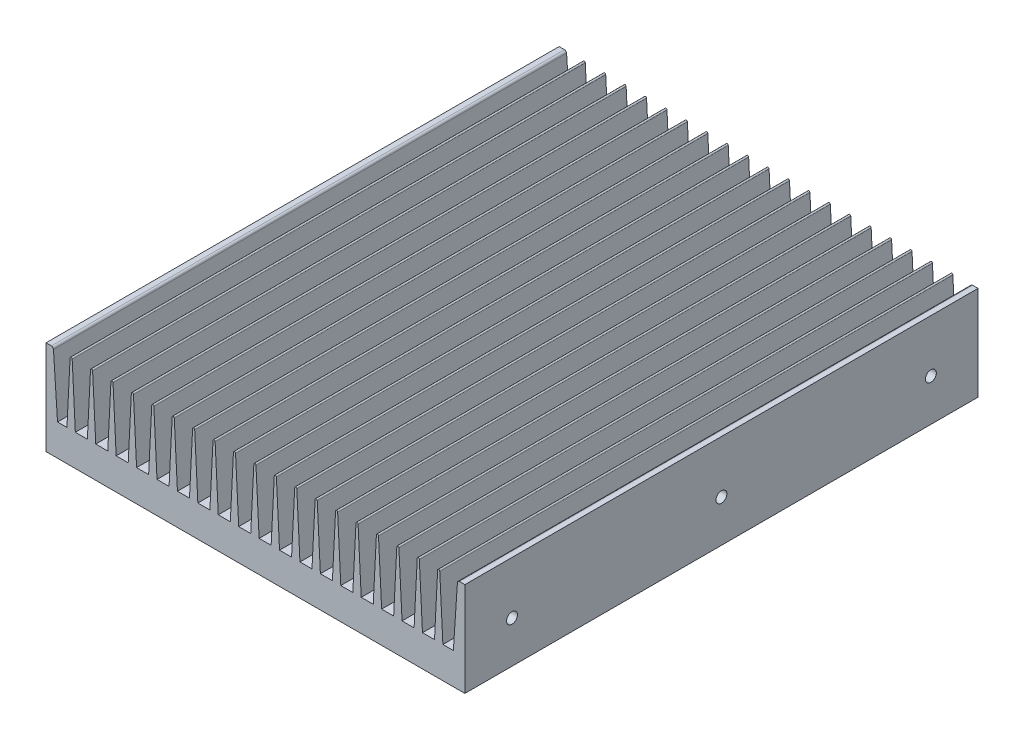
SolidWorks part; units mm, degrees
ref_plane "Спереди" through (0, 0, 0) normal (0, 0, 1) x (1, 0, 0)
ref_plane "Сверху" through (0, 0, 0) normal (0, 1, 0) x (1, 0, 0)
ref_plane "Справа" through (0, 0, 0) normal (1, 0, 0) x (0, 0, -1)
sketch "Эскиз1" plane through (0, 0, 0) normal (0, 0, 1) x (1, 0, 0)
  line L0 (0, 45) -> (2.5644, 45)
  line L1 (0, 0) -> (200, 0)
  line L2 (3.5622, 44.0665) -> (5.5, 15)
  line L3 (0, 45) -> (0, 0)
  line L4 (200, 45) -> (200, 0)
  line L5 (100, 63.7127) -> (100, -22.2582) construction
  line L8 (200, 45) -> (197.4356, 45)
  line L9 (196.4378, 44.0665) -> (194.5, 15)
  line L10 (5.5, 15) -> (194.5, 15)
  arc A0 (2.5644, 45) -> (3.5622, 44.0665) centre (2.5644, 44) cw
  arc A2 (197.4356, 45) -> (196.4378, 44.0665) centre (197.4356, 44) ccw
  point P18 (196.5, 45)
  dimension "D9" = 1
  dimension "D1" = 200
  dimension "D2" = 15
  dimension "D3" = 45
  dimension "D4" = 5.5
  dimension "D7" = 3.5
extrude "Вытянуть1" add sketch "Эскиз1" along normal blind 245
sketch "Эскиз2" plane through (0, 0, 245) normal (0, 0, 1) x (1, 0, 0)
  line L0 (194.5, 15) -> (5.5, 15) construction
  line L1 (11.5, 44.5) -> (10, 15)
  line L2 (12, 44.5) -> (12, 22.5548) construction
  line L3 (12.5, 44.5) -> (14, 15)
  line L4 (10, 15) -> (14, 15)
  line L6 (0, 45) -> (0, 0) construction
  arc A0 (11.5, 44.5) -> (12.5, 44.5) centre (12, 44.5) cw
  dimension "D1" = 30
  dimension "D3" = 0.5
  dimension "D2" = 4
  dimension "D4" = 12
  dimension "D5" = 1
extrude "Вытянуть3" add sketch "Эскиз2" against normal blind 245
pattern_curve "Кривая1" of "Вытянуть3" along edge at (100, 0, 0) parameters "D1"=19, "D3"=9.75, "D2"=1, "D4"=50
sketch "Эскиз7" plane through (0, 0, 0) normal (-1, 0, 0) x (0, 0, 1)
  line L0 (-24.1676, 20) -> (275.3481, 20) construction
  line L1 (122.5, 109.9776) -> (122.5, -31.6981) construction
  line L2 (245, 45) -> (245, 0) construction
  line L3 (0, 45) -> (0, 0) construction
  line L4 (245, 0) -> (0, 0) construction
  circle A0 centre (22.5, 20) radius 2.6
  circle A1 centre (222.5, 20) radius 2.6
  circle A2 centre (122.5, 20) radius 2.6
  dimension "D2" = 5.2
  dimension "D3" = 200
  dimension "D1" = 20
extrude "Вырез-Вытянуть4" cut sketch "Эскиз7" against normal blind 6
cosmetic thread "Условное изображение резьбы17" parameters "D1"=5.26, "D2"=6
cosmetic thread "Условное изображение резьбы18" parameters "D1"=5.26, "D2"=6
cosmetic thread "Условное изображение резьбы19" parameters "D1"=5.26, "D2"=6
cosmetic thread "Условное изображение резьбы37" parameters "D2"=6
cosmetic thread "Условное изображение резьбы38" parameters "D2"=6
cosmetic thread "Условное изображение резьбы39" parameters "D2"=6
sketch "Эскиз13" plane through (200, 0, 0) normal (1, 0, 0) x (0, 0, -1)
  circle A0 centre (-222.5, 20) radius 2.6 construction
  circle A1 centre (-222.5, 20) radius 2.6
  circle A2 centre (-122.5, 20) radius 2.6 construction
  circle A3 centre (-122.5, 20) radius 2.6
  circle A4 centre (-22.5, 20) radius 2.6 construction
  circle A5 centre (-22.5, 20) radius 2.6
extrude "Вырез-Вытянуть9" cut sketch "Эскиз13" against normal blind 8
cosmetic thread "Условное изображение резьбы34" parameters "D2"=6
cosmetic thread "Условное изображение резьбы35" parameters "D2"=6
cosmetic thread "Условное изображение резьбы36" parameters "D2"=6
sketch "Эскиз15" plane through (0, 0, 0) normal (0, -1, 0) x (1, 0, 0)
  line L0 (160, 95) -> (160, 230) construction
  line L1 (40, 95) -> (40, 230) construction
  line L2 (0, 245) -> (200, 245) construction
  line L3 (0, 245) -> (0, 0) construction
  line L5 (160, 230) -> (40, 230) construction
  line L6 (160, 95) -> (40, 95) construction
  line L8 (126.9868, 142.4) -> (75.6124, 142.4) construction
  line L10 (0, 0) -> (200, 0) construction
  circle A0 centre (45, 42) radius 2.1
  circle A6 centre (116.5, 142.4) radius 1.6
  circle A7 centre (83, 142.4) radius 1.6
  circle A8 centre (40, 230) radius 1.6
  circle A9 centre (160, 230) radius 1.6
  circle A10 centre (40, 95) radius 1.6
  circle A11 centre (160, 95) radius 1.6
  dimension "D2" = 120
  dimension "D3" = 15
  dimension "D4" = 40
  dimension "D5" = 4.2
  dimension "D6" = 135
  dimension "D7" = 45
  dimension "D8" = 33.5
  dimension "D10" = 42
  dimension "D13" = 3.2
  dimension "D14" = 87.6
  dimension "D9" = 43
  dimension "D15" = 3.2
extrude "Вырез-Вытянуть10" cut sketch "Эскиз15" against normal blind 10
cosmetic thread "Условное изображение резьбы40" parameters "D1"=8, "D2"=4
cosmetic thread "Условное изображение резьбы41" parameters "D1"=8, "D2"=4
cosmetic thread "Условное изображение резьбы42" parameters "D1"=8, "D2"=4
cosmetic thread "Условное изображение резьбы43" parameters "D1"=8, "D2"=4
cosmetic thread "Условное изображение резьбы48" parameters "D1"=8, "D2"=5
cosmetic thread "Условное изображение резьбы49" parameters "D1"=8, "D2"=4
cosmetic thread "Условное изображение резьбы50" parameters "D1"=8, "D2"=4
